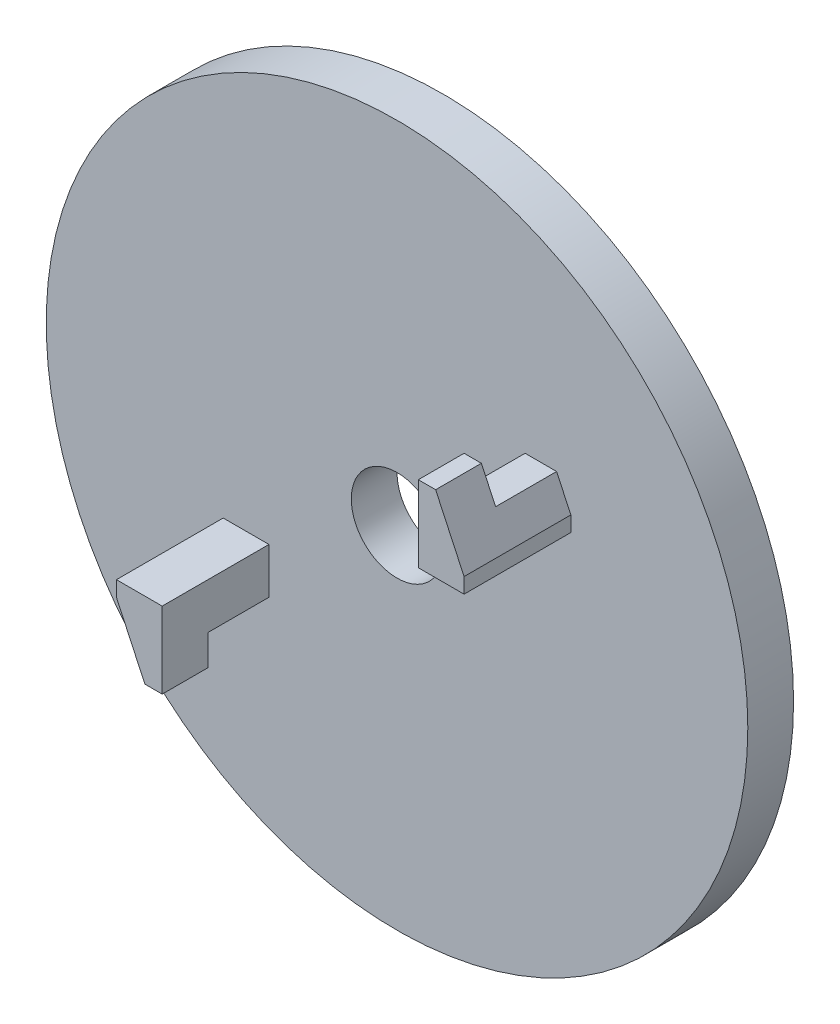
SolidWorks part; units mm, degrees
ref_plane "Front Plane" through (0, 0, 0) normal (0, 0, 1) x (1, 0, 0)
ref_plane "Top Plane" through (0, 0, 0) normal (0, 1, 0) x (1, 0, 0)
ref_plane "Right Plane" through (0, 0, 0) normal (1, 0, 0) x (0, 0, -1)
sketch "Sketch1" plane through (0, 0, 0) normal (0, 0, 1) x (1, 0, 0)
  circle A0 centre (0, 0) radius 11.5
  circle A1 centre (0, 0) radius 1.5
extrude "Boss-Extrude1" add sketch "Sketch1" along normal blind 1.5
sketch "Sketch2" plane through (0, 0, 1.5) normal (0, 0, 1) x (1, 0, 0)
  line L0 (0, 0) -> (4.9483, 3.3932) construction
  line L1 (0, 0) -> (-2.2072, 3.2188) construction
  line L2 (4.1983, 4.1432) -> (5.6983, 4.1432)
  line L3 (4.1983, 4.1432) -> (4.1983, 2.6432)
  line L4 (4.1983, 2.6432) -> (5.6983, 2.6432)
  line L5 (5.6983, 4.1432) -> (5.6983, 2.6432)
  line L6 (4.1983, 4.1432) -> (5.6983, 2.6432) construction
  line L7 (4.1983, 2.6432) -> (5.6983, 4.1432) construction
  line L8 (0, 0) -> (-4.9483, -3.3932) construction
  line L14 (-5.6983, -2.6432) -> (-4.1983, -2.6432)
  line L15 (-5.6983, -2.6432) -> (-5.6983, -4.1432)
  line L16 (-5.6983, -4.1432) -> (-4.1983, -4.1432)
  line L17 (-4.1983, -2.6432) -> (-4.1983, -4.1432)
  line L18 (-5.6983, -2.6432) -> (-4.1983, -4.1432) construction
  line L19 (-5.6983, -4.1432) -> (-4.1983, -2.6432) construction
  dimension "D1" = 1.5
  dimension "D2" = 1.5
  dimension "D3" = 6
  dimension "D4" = 1.5
  dimension "D5" = 1.5
extrude "Boss-Extrude3" add sketch "Sketch2" along normal blind 3.5
sketch "Sketch3" plane through (0, 4.1432, 0) normal (0, 1, 0) x (1, 0, 0)
  line L0 (4.1983, -5) -> (4.1983, -1.5) construction
  line L1 (5.6983, -5) -> (4.1983, -5)
  line L2 (5.6983, -5) -> (5.6983, -3.5)
  line L3 (5.6983, -3.5) -> (4.1983, -3.5)
  line L4 (4.1983, -5) -> (4.1983, -3.5)
  dimension "D1" = 1.5
extrude "Boss-Extrude4" add sketch "Sketch3" along normal blind 1
chamfer "Chamfer2" distance 2 angle 25 1 edges at (5.6983, 5.1432, 4.25)
sketch "Sketch5" plane through (0, -4.1432, 0) normal (0, -1, 0) x (1, 0, 0)
  line L0 (-5.6983, 5) -> (-5.6983, 1.5) construction
  line L1 (-4.1983, 5) -> (-5.6983, 5)
  line L2 (-4.1983, 5) -> (-4.1983, 3.5)
  line L3 (-4.1983, 3.5) -> (-5.6983, 3.5)
  line L4 (-5.6983, 5) -> (-5.6983, 3.5)
  dimension "D1" = 1.5
extrude "Boss-Extrude6" add sketch "Sketch5" along normal blind 1
chamfer "Chamfer5" distance 2 angle 25 1 edges at (-5.6983, -5.1432, 4.25)
